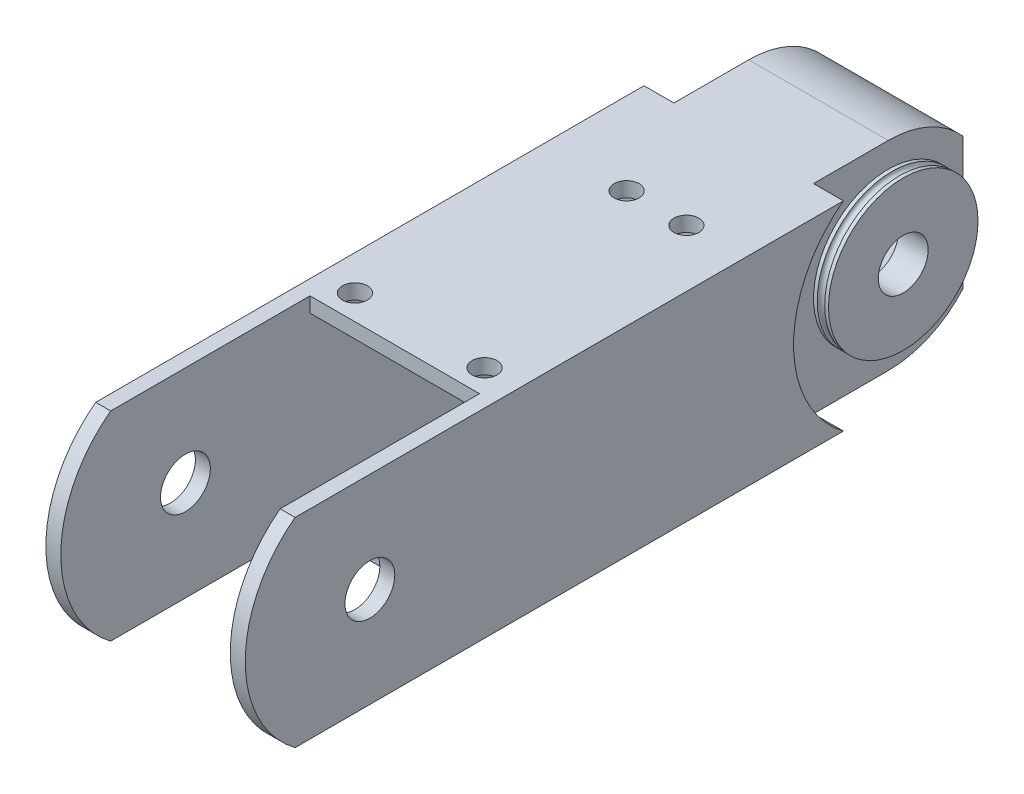
SolidWorks part; units mm, degrees
ref_plane "Alzado" through (0, 0, 0) normal (0, 0, 1) x (1, 0, 0)
ref_plane "Planta" through (0, 0, 0) normal (0, 1, 0) x (1, 0, 0)
ref_plane "Vista lateral" through (0, 0, 0) normal (1, 0, 0) x (0, 0, -1)
sketch "Croquis1" plane through (0, 0, 0) normal (0, 0, 1) x (1, 0, 0)
  line L1 (-20, -20) -> (20, -20)
  line L2 (-20, -20) -> (-20, 20)
  line L3 (-20, 20) -> (20, 20)
  line L4 (20, -20) -> (20, 20)
  line L5 (-20, -20) -> (20, 20) construction
  line L6 (-20, 20) -> (20, -20) construction
  point P0 (0, 0)
  dimension "D1" = 40
  dimension "D2" = 40
extrude "Saliente-Extruir1" add sketch "Croquis1" along normal blind 150
sketch "Croquis2" plane through (0, 0, 150) normal (0, 0, 1) x (1, 0, 0)
  line L0 (20, 20) -> (-20, 20) construction
  line L1 (-17, 20) -> (17, 20)
  line L2 (-17, 20) -> (-17, -20)
  line L3 (-17, -20) -> (17, -20)
  line L4 (17, 20) -> (17, -20)
  line L5 (-20, -20) -> (20, -20) construction
  line L6 (-20, 20) -> (-20, -20) construction
  line L7 (20, -20) -> (20, 20) construction
  dimension "D1" = 3
  dimension "D2" = 3
extrude "Cortar-Extruir1" cut sketch "Croquis2" against normal blind 50
sketch "Croquis3" plane through (20, 0, 0) normal (1, 0, 0) x (0, 0, -1)
  line L0 (-150, -20) -> (0, -20) construction
  line L1 (-150, 20) -> (-140, 20)
  line L2 (-150, 20) -> (-150, 0)
  line L3 (-150, -20) -> (-140, -20)
  line L4 (-150, 20) -> (0, 20) construction
  line L7 (-150, 0) -> (-150, -20)
  arc A0 (-140, 20) -> (-150, 0) centre (-125, 0) ccw
  arc A1 (-150, 0) -> (-140, -20) centre (-125, 0) ccw
  dimension "D1" = 25
  dimension "D2" = 10
extrude "Cortar-Extruir5" cut sketch "Croquis3" against normal through all contours L2 L1 A0 | L7 L3 A1
sketch "Croquis4" plane through (20, 0, 0) normal (1, 0, 0) x (0, 0, -1)
  circle A0 centre (-125, 0) radius 5
  dimension "D1" = 10
extrude "Cortar-Extruir6" cut sketch "Croquis4" against normal through all
sketch "Croquis8" plane through (20, 0, 0) normal (1, 0, 0) x (0, 0, -1)
  line L0 (-140, 20) -> (0, 20) construction
  line L1 (0, -20) -> (0, 20) construction
  line L2 (-140, -20) -> (0, -20) construction
  arc A0 (-15, 20) -> (0, 13.2288) centre (-15, 0) cw
  arc A1 (0, -13.2288) -> (-15, -20) centre (-15, 0) cw
  point P10 (0, 0)
  line M2 (0, 20) -> (-140, 20)
  line M4 (-140, -20) -> (0, -20)
  line M5 (0, -20) -> (0, 20)
  dimension "D1" = 20
  dimension "D3" = 20
  dimension "D2" = 15
  dimension "D4" = 15
extrude "Cortar-Extruir10" cut sketch "Croquis8" against normal through all contours A0 M2 M5 | A1 M5 M4
sketch "Croquis5" plane through (20, 0, 0) normal (1, 0, 0) x (0, 0, -1)
  line L0 (0, -13.2288) -> (0, 13.2288) construction
  circle A0 centre (-15, 0) radius 5
  point P4 (0, 0)
  dimension "D1" = 15
  dimension "D2" = 10
extrude "Cortar-Extruir7" cut sketch "Croquis5" against normal through all
sketch "Croquis6" plane through (20, 0, 0) normal (1, 0, 0) x (0, 0, -1)
  line L0 (-140, -20) -> (-15, -20) construction
  line L1 (-140, 20) -> (-15, 20) construction
  arc A0 (-30, -20) -> (-30, 20) centre (-15, 0) cw
  circle A2 centre (-15, 0) radius 5 construction
  circle M1 centre (-15, 0) radius 5
  line M3 (-15, 20) -> (-140, 20)
  line M5 (-140, -20) -> (-15, -20)
  line M6 (0, -13.2288) -> (0, 13.2288)
  arc M11 (-15, -20) -> (0, -13.2288) centre (-15, 0) ccw
  arc M12 (0, 13.2288) -> (-15, 20) centre (-15, 0) ccw
  dimension "D1" = 25
extrude "Cortar-Extruir8" cut sketch "Croquis6" against normal blind 6 contours A0 M5 M11 M6 M12 M3 M1
sketch "Croquis9" plane through (-20, 0, 0) normal (-1, 0, 0) x (0, 0, 1)
  line L0 (140, 20) -> (15, 20) construction
  line L1 (140, -20) -> (15, -20) construction
  arc A0 (30, 20) -> (30, -20) centre (15, 0) cw
  circle A1 centre (15, 0) radius 5 construction
  circle M1 centre (15, 0) radius 5
  line M3 (0, 13.2288) -> (0, -13.2288)
  arc M4 (0, -13.2288) -> (15, -20) centre (15, 0) ccw
  line M5 (15, -20) -> (140, -20)
  line M7 (140, 20) -> (15, 20)
  arc M8 (15, 20) -> (0, 13.2288) centre (15, 0) ccw
  dimension "D1" = 25
extrude "Cortar-Extruir11" cut sketch "Croquis9" against normal blind 6 contours A0 M7 M8 M3 M4 M5 M1
sketch "Croquis10" plane through (14, 0, 0) normal (1, 0, 0) x (0, 0, -1)
  circle A0 centre (-15, 0) radius 15
  circle A1 centre (-15, 0) radius 5 construction
  circle A2 centre (-15, 0) radius 5
  dimension "D1" = 30
extrude "Saliente-Extruir2" add sketch "Croquis10" along normal blind 3
sketch "Croquis11" plane through (-14, 0, 0) normal (-1, 0, 0) x (0, 0, 1)
  circle A0 centre (15, 0) radius 15
  circle A1 centre (15, 0) radius 5 construction
  circle A2 centre (15, 0) radius 5
  dimension "D1" = 30
extrude "Saliente-Extruir3" add sketch "Croquis11" along normal blind 3
ref_axis "Eje1" through (-18, 0, 15) along (1, 0, 0)
ref_plane "Plano1" through (0, 0, 15) normal (0, 0, 1) x (1, 0, 0)
sketch "Croquis12" plane through (0, 0, 15) normal (0, 0, 1) x (1, 0, 0)
  line L2 (17, 15) -> (14, 15) construction
  line L3 (-14, 15) -> (-17, 15) construction
  circle A0 centre (15.5, 15) radius 0.75
  circle A1 centre (-15.5, 15) radius 0.75
  dimension "D1" = 1.5
  dimension "D2" = 1.5
revolve "Cortar-Revolución1" cut sketch "Croquis12" angle 360 about axis through (-18, 0, 15) along (1, 0, 0)
sketch "Croquis13" plane through (0, -20, 0) normal (0, -1, 0) x (1, 0, 0)
  line L0 (-17, 100) -> (17, 100) construction
  line L1 (20, 140) -> (20, 30) construction
  line L2 (-20, 140) -> (-20, 30) construction
  circle A0 centre (13, 95) radius 2.5
  circle A1 centre (-13, 95) radius 2.5
  dimension "D1" = 5
  dimension "D2" = 5
  dimension "D3" = 5
  dimension "D4" = 5
  dimension "D5" = 7
  dimension "D6" = 7
extrude "Cortar-Extruir12" cut sketch "Croquis13" against normal through all
sketch "Croquis15" plane through (0, 0, 0) normal (0, 0, -1) x (-1, 0, 0)
  line L0 (14, 13.2288) -> (-14, 13.2288) construction
  line L1 (11, -10.2288) -> (-11, -10.2288)
  line L2 (11, -10.2288) -> (11, 10.2288)
  line L3 (11, 10.2288) -> (-11, 10.2288)
  line L4 (-11, -10.2288) -> (-11, 10.2288)
  line L5 (11, -10.2288) -> (-11, 10.2288) construction
  line L6 (11, 10.2288) -> (-11, -10.2288) construction
  line L7 (-14, 15) -> (-14, -15) construction
  point P0 (0, 0)
  dimension "D1" = 3
  dimension "D2" = 3
extrude "Cortar-Extruir14" cut sketch "Croquis15" against normal offset from surface (95 mm away) 5 up to face at (0, 0, 100)
sketch "Croquis17" plane through (0, 0, 100) normal (0, 0, 1) x (1, 0, 0)
  line L0 (-17, 20) -> (-17, -20) construction
  line L1 (17, -17) -> (-17, -17)
  line L2 (17, -17) -> (17, 17)
  line L3 (17, 17) -> (-17, 17)
  line L4 (-17, -17) -> (-17, 17)
  line L5 (17, -17) -> (-17, 17) construction
  line L6 (17, 17) -> (-17, -17) construction
  line L7 (-17, -20) -> (17, -20) construction
  point P0 (0, 0)
  dimension "D1" = 3
extrude "Cortar-Extruir15" cut sketch "Croquis17" against normal blind 55
sketch "Croquis18" plane through (0, 20, 0) normal (0, 1, 0) x (1, 0, 0)
  line L0 (20, -140) -> (20, -30) construction
  line L1 (-20, -140) -> (-20, -30) construction
  line L2 (17, -100) -> (-17, -100) construction
  circle A0 centre (8.5, -50) radius 2.5
  circle A1 centre (-3.5, -50) radius 2.5
  dimension "D1" = 5
  dimension "D2" = 5
  dimension "D3" = 11.5
  dimension "D4" = 16.5
  dimension "D5" = 50
  dimension "D6" = 50
extrude "Cortar-Extruir16" cut sketch "Croquis18" against normal through all
